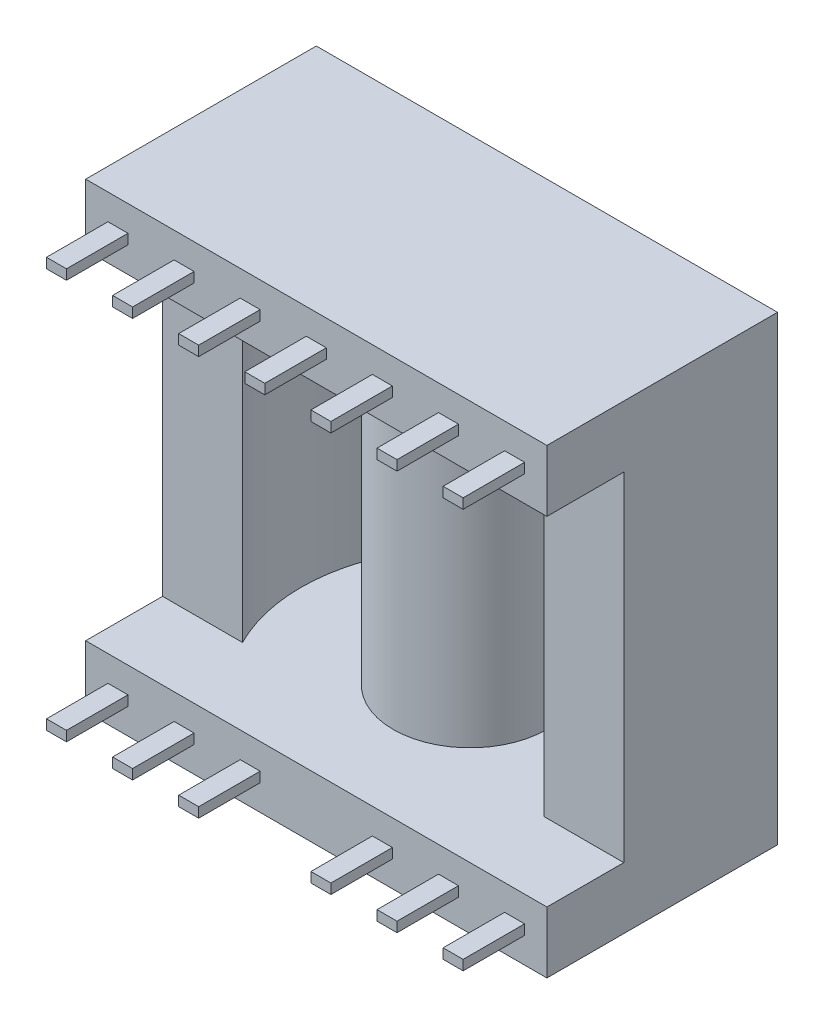
SolidWorks part; units mm, degrees
material "N87"
ref_plane "Спереди" through (0, 0, 0) normal (0, 0, 1) x (1, 0, 0)
ref_plane "Сверху" through (0, 0, 0) normal (0, 1, 0) x (1, 0, 0)
ref_plane "Справа" through (0, 0, 0) normal (1, 0, 0) x (0, 0, -1)
other "Configuration Table"
sketch "Эскиз1" plane through (0, 0, 0) normal (0, 1, 0) x (1, 0, 0)
  line L1 (0, 0) -> (30, 0)
  line L2 (0, 0) -> (0, 10)
  line L3 (0, 10) -> (30, 10)
  line L4 (30, 0) -> (30, 10)
  circle A0 centre (15, 5) radius 5
  circle A1 centre (15, 5) radius 11
  dimension "D3" = 22
  dimension "D4" = 10
  dimension "D1" = 30
  dimension "D2" = 10
  dimension "D5" = 5
  dimension "D6" = 15
extrude "Бобышка-Вытянуть1" add sketch "Эскиз1" along normal blind 11 contours A1 L3 L2 L1 | A0 | A1 L1 L4 L3
sketch "Эскиз2" plane through (0, 0, 0) normal (0, -1, 0) x (1, 0, 0)
  line L1 (0, 0) -> (30, 0)
  line L2 (0, 0) -> (0, -10)
  line L3 (0, -10) -> (30, -10)
  line L4 (30, 0) -> (30, -10)
extrude "Бобышка-Вытянуть2" add sketch "Эскиз2" along normal blind 4
sketch "Эскиз3" plane through (0, 11, 0) normal (0, 1, 0) x (1, 0, 0)
  line L0 (24.798, 0) -> (30, 0) construction
  line L1 (30, 0) -> (30, 10) construction
  line L2 (30, 10) -> (24.798, 10) construction
  line L3 (5.202, 10) -> (0, 10) construction
  line L4 (0, 10) -> (0, 0) construction
  line L5 (0, 0) -> (5.202, 0) construction
  line L6 (24.798, 0) -> (30, 0)
  line L7 (30, 0) -> (30, 10)
  line L8 (30, 10) -> (24.798, 10)
  line L9 (5.202, 10) -> (0, 10)
  line L10 (0, 10) -> (0, 0)
  line L11 (0, 0) -> (5.202, 0)
  arc A0 (24.798, 0) -> (24.798, 10) centre (15, 5) ccw construction
  arc A1 (5.202, 10) -> (5.202, 0) centre (15, 5) ccw construction
  circle A2 centre (15, 5) radius 5 construction
  arc A3 (24.798, 0) -> (24.798, 10) centre (15, 5) ccw
  arc A4 (5.202, 10) -> (5.202, 0) centre (15, 5) ccw
  circle A5 centre (15, 5) radius 5
extrude "Бобышка-Вытянуть3" add sketch "Эскиз3" along normal blind 11
sketch "Эскиз4" plane through (0, 22, 0) normal (0, 1, 0) x (1, 0, 0)
  line L1 (0, 10) -> (30, 10)
  line L2 (0, 10) -> (0, 0)
  line L3 (0, 0) -> (30, 0)
  line L4 (30, 10) -> (30, 0)
extrude "Бобышка-Вытянуть4" add sketch "Эскиз4" along normal blind 4
sketch "Эскиз5" plane through (0, 0, 0) normal (0, 0, 1) x (1, 0, 0)
  line L0 (30, -4) -> (30, 26) construction
  line L1 (0, 26) -> (30, 26)
  line L2 (0, 26) -> (0, 22)
  line L3 (0, 22) -> (30, 22)
  line L4 (30, 26) -> (30, 22)
  line L5 (15, 22) -> (24.798, 22) construction
  line L6 (0, 26) -> (0, -4) construction
  line L7 (30, -4) -> (0, -4)
  line L8 (30, -4) -> (30, 0)
  line L9 (30, 0) -> (0, 0)
  line L10 (0, -4) -> (0, 0)
  line L11 (15, 0) -> (5.202, 0) construction
extrude "Бобышка-Вытянуть5" add sketch "Эскиз5" along normal blind 5
sketch "Эскиз6" plane through (0, 0, 5) normal (0, 0, 1) x (1, 0, 0)
  line L0 (5.75, 23.675) -> (5.75, 24.325)
  line L1 (1.45, 23.675) -> (2.75, 23.675)
  line L2 (1.45, 23.675) -> (1.45, 24.325)
  line L3 (1.45, 24.325) -> (2.75, 24.325)
  line L4 (2.75, 23.675) -> (2.75, 24.325)
  line L5 (5.75, 23.675) -> (7.05, 23.675)
  line L6 (7.05, 23.675) -> (7.05, 24.325)
  line L7 (5.75, 24.325) -> (7.05, 24.325)
  line L8 (10.05, 23.675) -> (10.05, 24.325)
  line L9 (10.05, 23.675) -> (11.35, 23.675)
  line L10 (11.35, 23.675) -> (11.35, 24.325)
  line L11 (10.05, 24.325) -> (11.35, 24.325)
  line L12 (14.35, 23.675) -> (14.35, 24.325)
  line L13 (14.35, 23.675) -> (15.65, 23.675)
  line L14 (15.65, 23.675) -> (15.65, 24.325)
  line L15 (14.35, 24.325) -> (15.65, 24.325)
  line L16 (18.65, 23.675) -> (18.65, 24.325)
  line L17 (18.65, 23.675) -> (19.95, 23.675)
  line L18 (19.95, 23.675) -> (19.95, 24.325)
  line L19 (18.65, 24.325) -> (19.95, 24.325)
  line L20 (22.95, 23.675) -> (22.95, 24.325)
  line L21 (22.95, 23.675) -> (24.25, 23.675)
  line L22 (24.25, 23.675) -> (24.25, 24.325)
  line L23 (22.95, 24.325) -> (24.25, 24.325)
  line L24 (27.25, 23.675) -> (27.25, 24.325)
  line L25 (27.25, 23.675) -> (28.55, 23.675)
  line L26 (28.55, 23.675) -> (28.55, 24.325)
  line L27 (27.25, 24.325) -> (28.55, 24.325)
  line L28 (30, 26) -> (0, 26) construction
  line L29 (30, 22) -> (30, 26) construction
  line L30 (5.75, -1.675) -> (5.75, -2.325)
  line L31 (1.45, -1.675) -> (2.75, -1.675)
  line L32 (1.45, -1.675) -> (1.45, -2.325)
  line L33 (1.45, -2.325) -> (2.75, -2.325)
  line L34 (2.75, -1.675) -> (2.75, -2.325)
  line L35 (5.75, -1.675) -> (7.05, -1.675)
  line L36 (7.05, -1.675) -> (7.05, -2.325)
  line L37 (5.75, -2.325) -> (7.05, -2.325)
  line L38 (10.05, -1.675) -> (10.05, -2.325)
  line L39 (10.05, -1.675) -> (11.35, -1.675)
  line L40 (11.35, -1.675) -> (11.35, -2.325)
  line L41 (10.05, -2.325) -> (11.35, -2.325)
  line L42 (30, 0) -> (0, 0) construction
  line L43 (22.95, -1.675) -> (22.95, -2.325)
  line L44 (18.65, -1.675) -> (19.95, -1.675)
  line L45 (18.65, -1.675) -> (18.65, -2.325)
  line L46 (18.65, -2.325) -> (19.95, -2.325)
  line L47 (19.95, -1.675) -> (19.95, -2.325)
  line L48 (22.95, -1.675) -> (24.25, -1.675)
  line L49 (24.25, -1.675) -> (24.25, -2.325)
  line L50 (22.95, -2.325) -> (24.25, -2.325)
  line L51 (27.25, -1.675) -> (27.25, -2.325)
  line L52 (27.25, -1.675) -> (28.55, -1.675)
  line L53 (28.55, -1.675) -> (28.55, -2.325)
  line L54 (27.25, -2.325) -> (28.55, -2.325)
  line L55 (30, 0) -> (24.798, 0) construction
  point P30 (1.45, 24)
  point P31 (15, 24.325)
  point P39 (1.45, -2)
  point P49 (6.4, 23.675)
  point P50 (6.4, -1.675)
  point P56 (27.25, -2)
  point P66 (23.6, 23.675)
  point P67 (23.6, -1.675)
  dimension "D2" = 0.65
  dimension "D3" = 1.3
  dimension "D4" = 3
  dimension "D5" = 2
  dimension "D6" = 15
  dimension "D8" = 1.3
  dimension "D9" = 0.65
  dimension "D10" = 2
  dimension "D11" = 3
  dimension "D13" = 1.3
  dimension "D14" = 0.65
  dimension "D15" = 3
  dimension "D16" = 2
  dimension "D1" = 7
  dimension "D7" = 3
  dimension "D12" = 3
extrude "Бобышка-Вытянуть6" add sketch "Эскиз6" along normal blind 4
